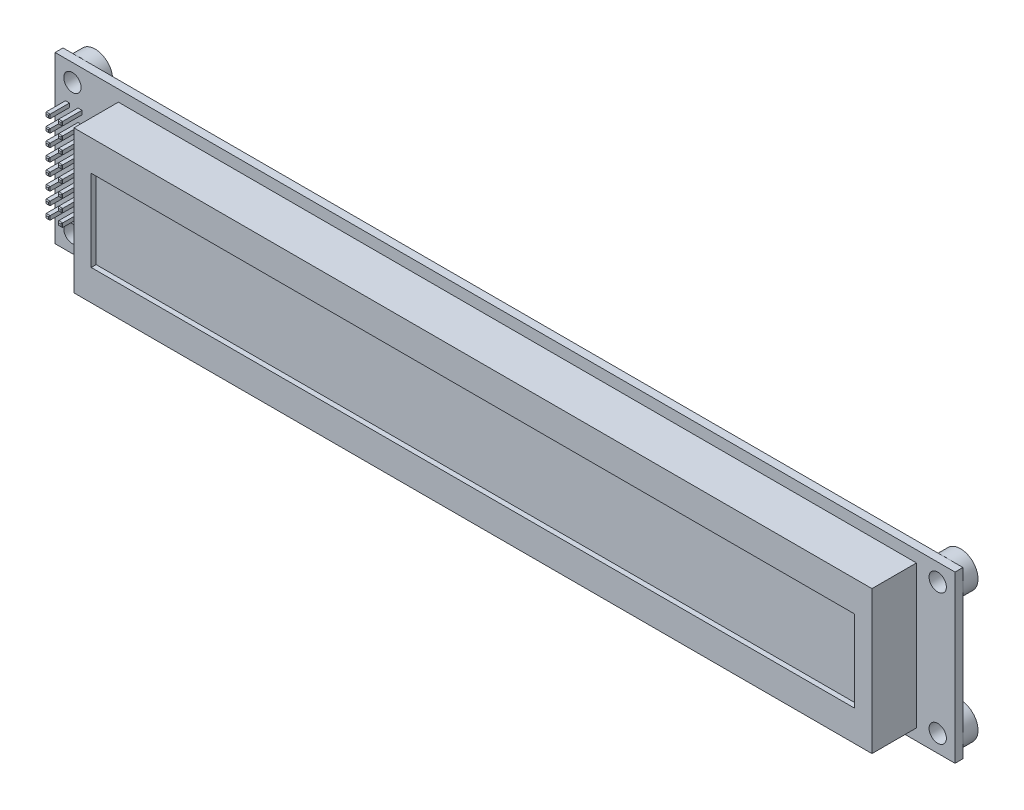
SolidWorks part; units mm, degrees
ref_plane "Спереди" through (0, 0, 0) normal (0, 0, 1) x (1, 0, 0)
ref_plane "Сверху" through (0, 0, 0) normal (0, 1, 0) x (1, 0, 0)
ref_plane "Справа" through (0, 0, 0) normal (1, 0, 0) x (0, 0, -1)
ref_plane "Плоскость4" through (0, 0, -6.6) normal (0, 0, 1) x (1, 0, 0)
sketch "Эскиз2" plane through (0, 0, -6.6) normal (0, 0, 1) x (1, 0, 0)
  line L1 (-91, -16.75) -> (91, -16.75)
  line L2 (-91, -16.75) -> (-91, 16.75)
  line L3 (-91, 16.75) -> (91, 16.75)
  line L4 (91, -16.75) -> (91, 16.75)
  line L5 (-91, -16.75) -> (91, 16.75) construction
  line L6 (-91, 16.75) -> (91, -16.75) construction
  point P0 (0, 0)
  dimension "D1" = 182
  dimension "D2" = 33.5
extrude "Бобышка-Вытянуть1" add sketch "Эскиз2" along normal blind 1.6
ref_plane "Плоскость5" through (0, 0, 0) normal (0, -1, 0) x (-1, 0, 0)
sketch "Эскиз3" plane through (0, 0, -5) normal (0, 0, 1) x (1, 0, 0)
  line L0 (-0.88, 0) -> (0.88, 0) construction
  line L1 (-78.2, 14.45) -> (83.2, 14.45)
  line L2 (-78.2, 14.45) -> (-78.2, -14.45)
  line L3 (-78.2, -14.45) -> (83.2, -14.45)
  line L4 (83.2, 14.45) -> (83.2, -14.45)
  line L5 (-78.2, 14.45) -> (83.2, -14.45) construction
  line L6 (-78.2, -14.45) -> (83.2, 14.45) construction
  line L7 (-91, 16.75) -> (-91, -16.75) construction
  point P0 (2.5, 0)
  dimension "D1" = 93.5
  dimension "D2" = 161.4
  dimension "D3" = 28.9
extrude "Бобышка-Вытянуть2" add sketch "Эскиз3" along normal blind 9
sketch "Эскиз4" plane through (0, 0, 4) normal (0, 0, 1) x (1, 0, 0)
  line L0 (-0.88, 0) -> (0.88, 0) construction
  line L1 (79.7, -8.25) -> (-74.7, -8.25)
  line L2 (79.7, -8.25) -> (79.7, 8.25)
  line L3 (79.7, 8.25) -> (-74.7, 8.25)
  line L4 (-74.7, -8.25) -> (-74.7, 8.25)
  line L5 (79.7, -8.25) -> (-74.7, 8.25) construction
  line L6 (79.7, 8.25) -> (-74.7, -8.25) construction
  line L7 (-91, 16.75) -> (-91, -16.75) construction
  point P0 (2.5, 0)
  dimension "D1" = 154.4
  dimension "D2" = 16.5
  dimension "D3" = 16.3
extrude "Вырез-Вытянуть1" cut sketch "Эскиз4" against normal blind 1
sketch "Эскиз5" plane through (0, 0, -5) normal (0, 0, 1) x (1, 0, 0)
  line L0 (-91, -16.75) -> (91, -16.75) construction
  line L1 (-91, 16.75) -> (-91, -16.75) construction
  circle A0 centre (-87.5, 13.25) radius 1.75
  circle A1 centre (-87.5, -13.25) radius 1.75
  circle A2 centre (87.5, -13.25) radius 1.75
  circle A3 centre (87.5, 13.25) radius 1.75
  dimension "D3" = 3.5
  dimension "D1" = 26.5
  dimension "D2" = 3.5
  dimension "D4" = 3.5
  dimension "D5" = 175
sketch "Эскиз6" plane through (0, 0, -6.6) normal (0, 0, -1) x (-1, 0, 0)
  circle A0 centre (-87.5, -13.25) radius 3.55
  circle A1 centre (-87.5, 13.25) radius 3.55
  circle A2 centre (87.5, 13.25) radius 3.55
  circle A3 centre (87.5, -13.25) radius 3.55
  dimension "D1" = 7.1
extrude "Бобышка-Вытянуть3" add sketch "Эскиз6" along normal blind 3
ref_plane "Плоскость6" through (0, 0, -9.6) normal (0, 0, -1) x (-1, 0, 0)
extrude "Вырез-Вытянуть2" cut sketch "Эскиз5" against normal through all both and the other way through all
sketch "Эскиз9" plane through (0, 0, -9.6) normal (0, 0, 1) x (1, 0, 0)
  line L0 (-0.88, 0) -> (0.88, 0) construction
  line L1 (-89.73, 10.16) -> (-84.73, 10.16)
  line L2 (-89.73, 10.16) -> (-89.73, -10.16)
  line L3 (-89.73, -10.16) -> (-84.73, -10.16)
  line L4 (-84.73, 10.16) -> (-84.73, -10.16)
  line L5 (-89.73, 10.16) -> (-84.73, -10.16) construction
  line L6 (-89.73, -10.16) -> (-84.73, 10.16) construction
  line L7 (-91, 16.75) -> (-91, -16.75) construction
  point P0 (-87.23, 0)
  dimension "D1" = 5
  dimension "D2" = 20.32
  dimension "D3" = 3.77
extrude "Бобышка-Вытянуть5" add sketch "Эскиз9" along normal blind 2.5
sketch "Эскиз10" plane through (0, 0, -7.1) normal (0, 0, 1) x (1, 0, 0)
  line L0 (91, 16.75) -> (-91, 16.75) construction
  line L1 (-88.9, 9.35) -> (-88.1, 9.35)
  line L2 (-88.9, 9.35) -> (-88.9, 8.55)
  line L3 (-88.9, 8.55) -> (-88.1, 8.55)
  line L4 (-88.1, 9.35) -> (-88.1, 8.55)
  line L5 (-88.9, 9.35) -> (-88.1, 8.55) construction
  line L6 (-88.9, 8.55) -> (-88.1, 9.35) construction
  point P0 (-88.5, 8.95)
  dimension "D1" = 0.8
  dimension "D2" = 0.8
  dimension "D3" = 1.27
  dimension "D4" = 7.8
extrude "Бобышка-Вытянуть6" add sketch "Эскиз10" along normal blind 6.2 and the other way blind 5.7 separate body
chamfer "Фаска1" distance 0.2 angle 39 8 edges at (-88.5, 9.35, -12.8) (-88.9, 8.95, -12.8) (-88.5, 8.55, -12.8) (-88.1, 8.95, -12.8) (-88.1, 8.95, -0.9) (-88.5, 9.35, -0.9) (-88.9, 8.95, -0.9) (-88.5, 8.55, -0.9)
pattern_linear "Линейный массив1" count 2 spacing 2.54 along (1, 0, 0) count 8 spacing 2.54 along (0, -1, 0) of "Бобышка-Вытянуть6"
ref_plane "Плоскость8" [suppressed] through (2.5, 0, 0) normal (-1, 0, 0) x (0, 0, 1)
